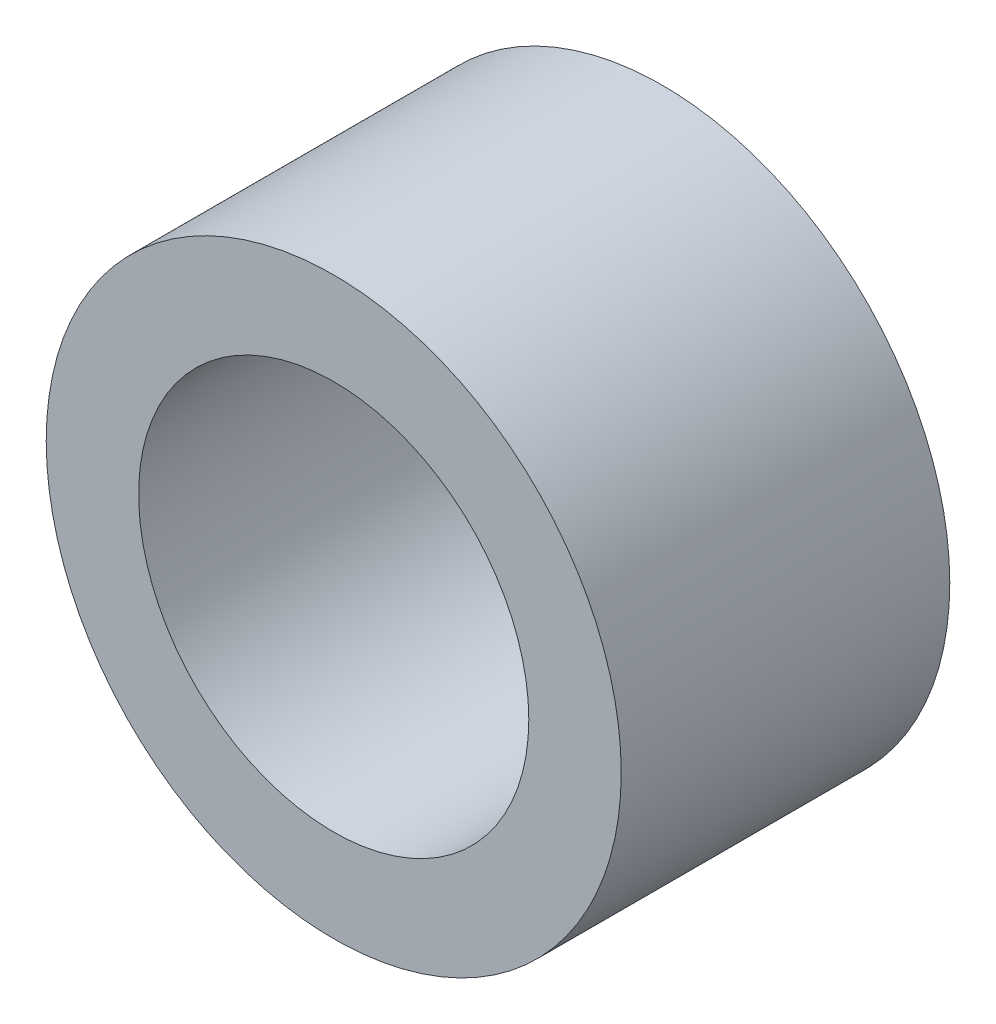
SolidWorks part; units mm, degrees
ref_plane "前视基准面" through (0, 0, 0) normal (0, 0, 1) x (1, 0, 0)
ref_plane "上视基准面" through (0, 0, 0) normal (0, 1, 0) x (1, 0, 0)
ref_plane "右视基准面" through (0, 0, 0) normal (1, 0, 0) x (0, 0, -1)
other "Configuration Table"
sketch "草图1" plane through (0, 0, 0) normal (1, 0, 0) x (0, 0, -1)
  line L0 (0, 0) -> (0, 18.5)
  line L1 (0, 18.5) -> (-16, 18.5)
  line L2 (-16, 18.5) -> (-16, 23)
  line L3 (-16, 23) -> (0, 23)
  line L4 (0, 23) -> (0, 18.5)
  line L5 (0, 0) -> (0, -0.5)
  line L6 (0, -0.5) -> (-16, -0.5)
  line L7 (-16, -0.5) -> (-16, -5)
  line L8 (-16, -5) -> (0, -5)
  line L9 (0, -5) -> (0, -0.5)
  line L10 (0, -0.5) -> (0, 18.5)
  line L11 (-28.3903, 9) -> (39.355, 9) construction
  dimension "D1" = 5
  dimension "D2" = 19
  dimension "D3" = 28
  dimension "D4" = 16
  dimension "D5" = 16
revolve "旋转2" add sketch "草图1" angle 360 about L11
sketch "草图3" plane through (0, 0, 0) normal (1, 0, 0) x (0, 0, -1)
  line L0 (0, 18.5) -> (-16, 18.5) construction
  line L1 (0, 18.5) -> (-16, 18.5) construction
  line L2 (0, 4.5) -> (32, 26.9066)
  line L3 (0, 0) -> (0, 18.5) construction
  line L4 (32, 26.9066) -> (32, 14)
  line L5 (1.7797, -4.7631) -> (17.7825, 8.7888)
  line L6 (-6.7082, -5) -> (61.4289, -5) construction
  line L7 (-16, -5) -> (0, -5) construction
  line L8 (32, 26.9066) -> (32, -35.4235) construction
  line L9 (1.1335, -5) -> (0, -5)
  line L10 (0, -5) -> (0, 4.5)
  line L11 (-26.5497, 9) -> (66.6128, 9) construction
  line L12 (6.4267, 9) -> (18.0358, 9)
  line L13 (-28.3903, 9) -> (39.355, 9) construction
  arc A0 (32, 14) -> (17.7825, 8.7888) centre (32, -8) ccw
  arc A1 (1.1335, -5) -> (1.7797, -4.7631) centre (1.1335, -4) ccw
  point P9 (0, 0)
  point P19 (1.5, -5)
  dimension "D4" = 44
  dimension "D6" = 1
  dimension "D1" = 14
  dimension "D2" = 32
  dimension "D3" = 55
  dimension "D5" = 1.5
  dimension "D7" = 3
